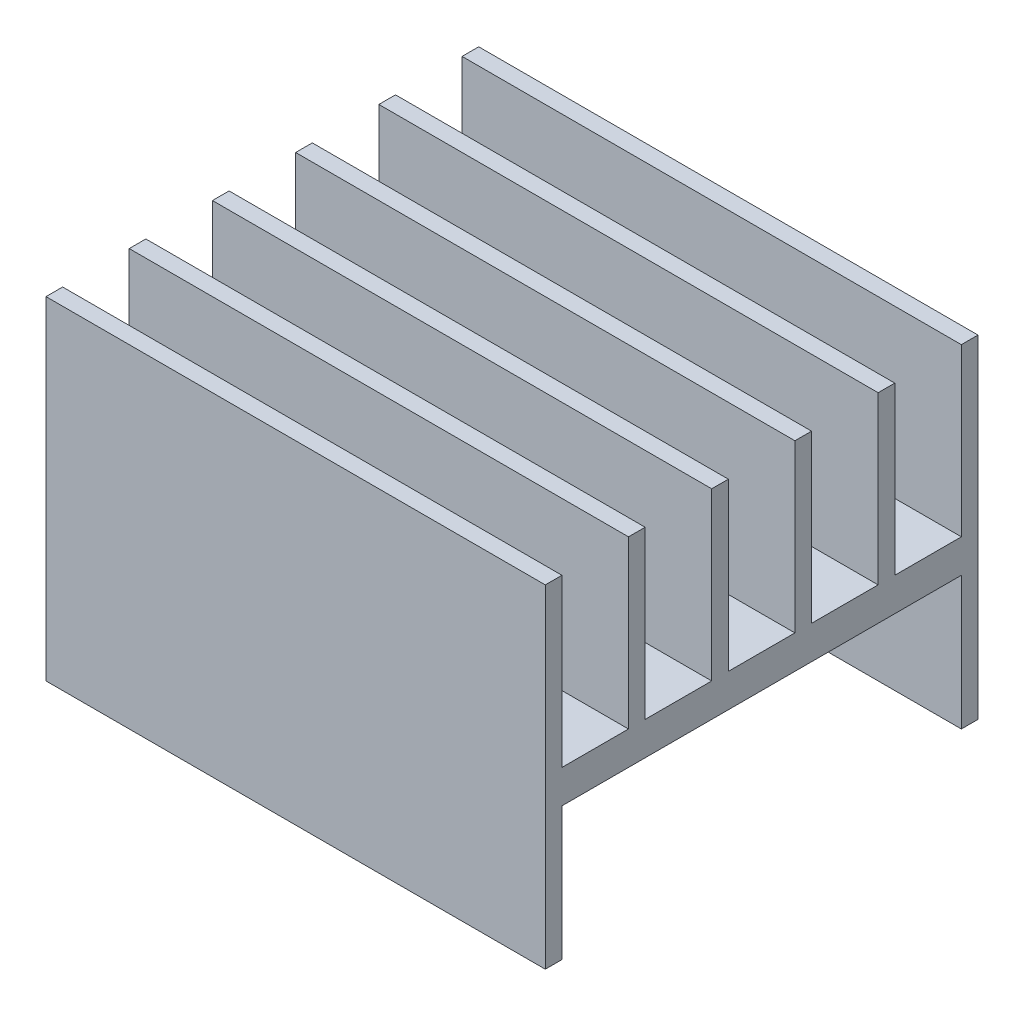
SolidWorks part; units mm, degrees
ref_plane "前视基准面" through (0, 0, 0) normal (0, 0, 1) x (1, 0, 0)
ref_plane "上视基准面" through (0, 0, 0) normal (0, 1, 0) x (1, 0, 0)
ref_plane "右视基准面" through (0, 0, 0) normal (1, 0, 0) x (0, 0, -1)
sketch "草图1" plane through (0, 0, 0) normal (1, 0, 0) x (0, 0, -1)
  line L0 (0, 66.7608) -> (0, -60.3349) construction
  line L1 (2, 0) -> (-2, 0)
  line L2 (-2, 0) -> (-2, 10)
  line L3 (-2, 10) -> (-3, 10)
  line L4 (-3, 10) -> (-3, 0)
  line L5 (-3, 0) -> (-7, 0)
  line L6 (-7, 0) -> (-7, 10)
  line L7 (-7, 10) -> (-8, 10)
  line L8 (-8, 10) -> (-8, 0)
  line L9 (-8, 0) -> (-12, 0)
  line L10 (-12, 0) -> (-12, 10)
  line L11 (-12, 10) -> (-13, 10)
  line L12 (-13, 10) -> (-13, -10)
  line L13 (-13, -10) -> (-12, -10)
  line L14 (-12, -10) -> (-12, -2)
  line L15 (-12, -2) -> (12, -2)
  line L16 (12, -10) -> (12, -2)
  line L17 (13, -10) -> (12, -10)
  line L18 (13, 10) -> (13, -10)
  line L19 (12, 10) -> (13, 10)
  line L20 (12, 0) -> (12, 10)
  line L21 (8, 0) -> (12, 0)
  line L22 (8, 10) -> (8, 0)
  line L23 (7, 10) -> (8, 10)
  line L24 (7, 0) -> (7, 10)
  line L25 (3, 0) -> (7, 0)
  line L26 (3, 10) -> (3, 0)
  line L27 (2, 10) -> (3, 10)
  line L28 (2, 0) -> (2, 10)
  point P20 (0, -2)
  point P33 (0, 0)
  dimension "D1" = 10
  dimension "D2" = 10
  dimension "D3" = 10
  dimension "D4" = 20
  dimension "D5" = 2
  dimension "D6" = 1
  dimension "D7" = 1
  dimension "D8" = 1
  dimension "D9" = 2
  dimension "D10" = 4
  dimension "D11" = 4
extrude "凸台-拉伸1" add sketch "草图1" along normal blind 30
